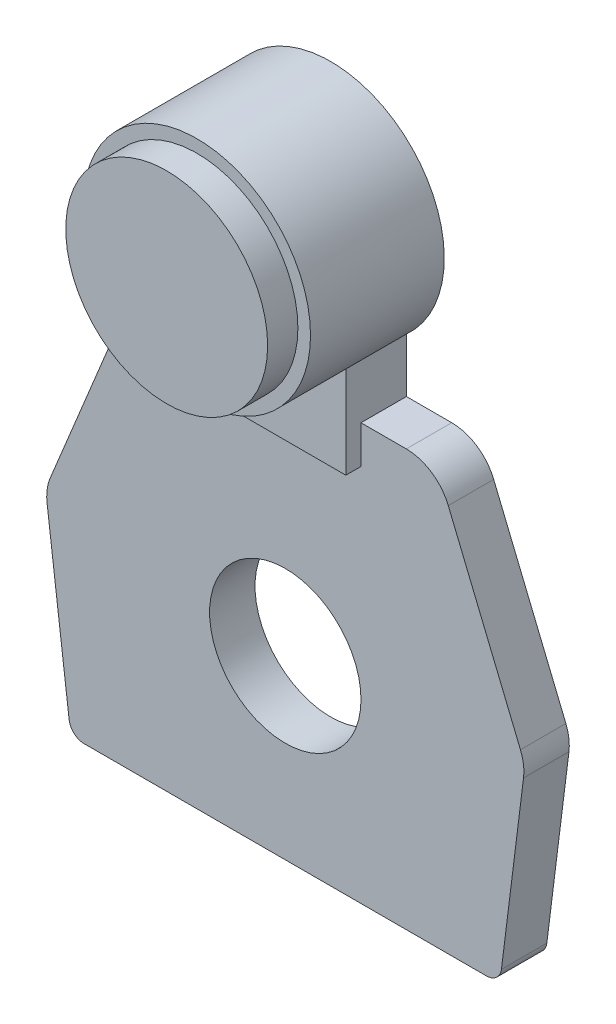
SolidWorks part; units mm, degrees
ref_plane "Front Plane" through (0, 0, 0) normal (0, 0, 1) x (1, 0, 0)
ref_plane "Top Plane" through (0, 0, 0) normal (0, 1, 0) x (1, 0, 0)
ref_plane "Right Plane" through (0, 0, 0) normal (1, 0, 0) x (0, 0, -1)
other "Configuration Table"
sketch "Sketch1" plane through (0, 0, 0) normal (0, 0, 1) x (1, 0, 0)
  line L0 (-79.7033, -70) -> (79.7033, -70)
  line L1 (85.657, -64.7442) -> (94.4121, 5.2967)
  line L2 (93.1953, 14.3829) -> (64.5897, 83.8535)
  line L3 (47.9455, 95) -> (-47.9455, 95)
  line L4 (-64.5897, 83.8535) -> (-93.1953, 14.3829)
  line L5 (-94.4121, 5.2967) -> (-85.657, -64.7442)
  arc A0 (-85.657, -64.7442) -> (-79.7033, -70) centre (-79.7033, -64) ccw
  arc A1 (79.7033, -70) -> (85.657, -64.7442) centre (79.7033, -64) ccw
  arc A2 (94.4121, 5.2967) -> (93.1953, 14.3829) centre (76.5511, 7.5294) ccw
  arc A3 (64.5897, 83.8535) -> (47.9455, 95) centre (47.9455, 77) ccw
  arc A4 (-47.9455, 95) -> (-64.5897, 83.8535) centre (-47.9455, 77) ccw
  arc A5 (-93.1953, 14.3829) -> (-94.4121, 5.2967) centre (-76.5511, 7.5294) ccw
extrude "Cover" add sketch "Sketch1" along normal blind 18 from offset 72
sketch "Sketch2" plane through (0, 0, 0) normal (0, 0, 1) x (1, 0, 0)
  line L0 (-30, 80) -> (30, 80)
  line L1 (30, 80) -> (30, 150)
  line L2 (30, 150) -> (-30, 150)
  line L3 (-30, 150) -> (-30, 80)
extrude "Pump Web" add sketch "Sketch2" along normal blind 24 from offset 72
sketch "Sketch3" plane through (0, 0, 0) normal (0, 0, 1) x (1, 0, 0)
  circle A0 centre (0, 150) radius 45
extrude "Water Pump" add sketch "Sketch3" along normal blind 53 from offset 72
sketch "Sketch4" plane through (0, 0, 0) normal (0, 0, 1) x (1, 0, 0)
  circle A0 centre (0, 150) radius 40
extrude "Pump Pulley" add sketch "Sketch4" along normal blind 12 from offset 125
sketch "Sketch5" plane through (0, 0, 0) normal (0, 0, 1) x (1, 0, 0)
  circle A0 centre (0, 0) radius 30
extrude "Seal Bore" cut sketch "Sketch5" against normal through all and the other way through all
